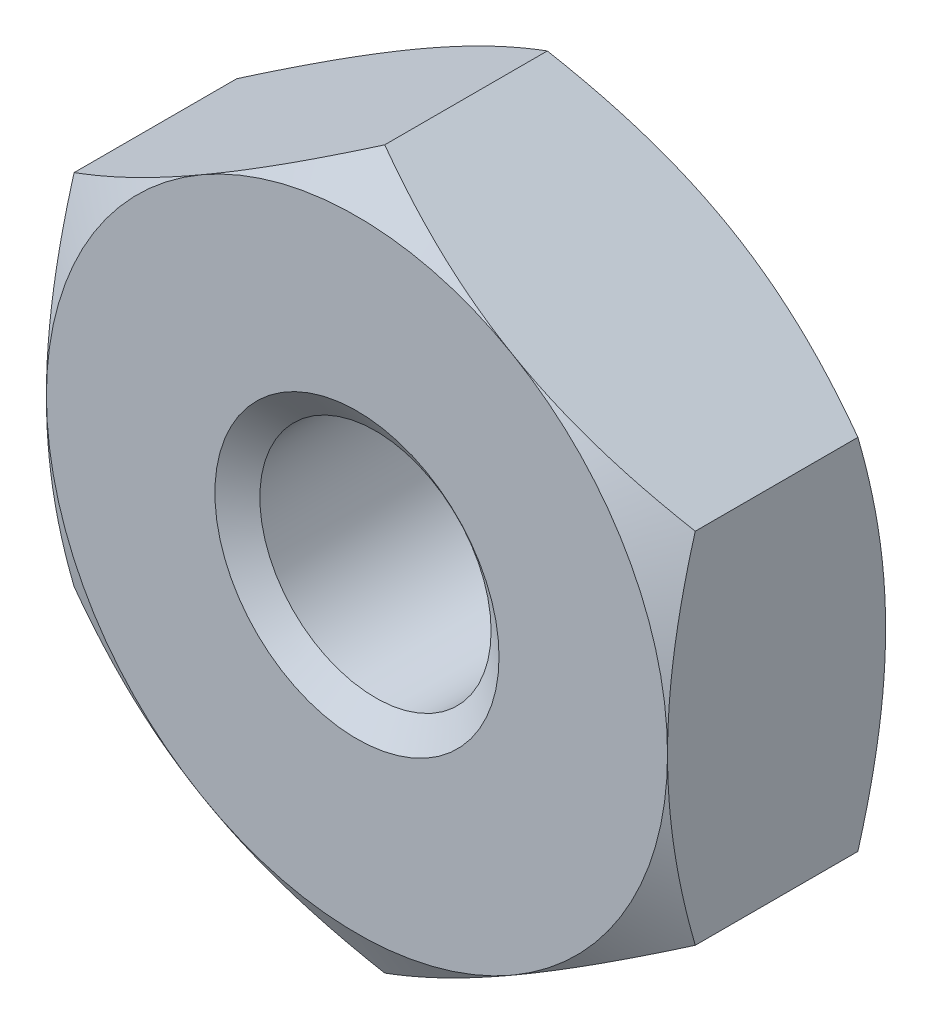
SolidWorks part; units mm, degrees
material "Alloy Steel"
ref_plane "Plane1" through (0, 0, 0) normal (0, 0, 1) x (1, 0, 0)
ref_plane "Plane2" through (0, 0, 0) normal (0, 1, 0) x (1, 0, 0)
ref_plane "Plane3" through (0, 0, 0) normal (1, 0, 0) x (0, 0, -1)
revolve "EndChamfer" cut sketch "EndChamferSketch" angle 360 about L11
sketch "EndChamferSketch" plane through (0, 0, 0) normal (1, 0, 0) x (0, 0, -1)
  line L0 (1.651, 1.0922) -> (1.4945, 0.8687)
  line L1 (1.7018, 1.0922) -> (1.651, 1.0922)
  line L2 (1.7018, 1.0922) -> (1.7018, 0.8687)
  line L3 (1.7018, 0.8687) -> (1.4945, 0.8687)
  line L6 (-0.0508, 1.0922) -> (0, 1.0922)
  line L7 (0, 1.0922) -> (0.1565, 0.8687)
  line L9 (0.1565, 0.8687) -> (-0.0508, 0.8687)
  line L10 (-0.0508, 0.8687) -> (-0.0508, 1.0922)
  line L11 (25.0375, 0) -> (38.388, 0) construction
  dimension "D1" = 35
  dimension "D2" = 0.0508
  dimension "Offset1" = 1.7018
  dimension "ThreadMajor" = 1.0922
  dimension "ChamferDepth" = 0.2235
  dimension "Offset2" = 1.7526
extrude "BaseNut" add sketch "BaseNutSke" against normal blind 1.6764
sketch "BaseNutSke" plane through (0, 0, 0) normal (0, 0, 1) x (1, 0, 0)
  line L6 (2.3876, 1.3785) -> (2.3876, -1.3785)
  line L7 (-2.3876, 1.3785) -> (-2.3876, -1.3785)
  line L8 (2.3876, 1.3785) -> (0, 2.757)
  line L9 (0, 2.757) -> (-2.3876, 1.3785)
  line L10 (-2.3876, -1.3785) -> (0, -2.757)
  line L11 (0, -2.757) -> (2.3876, -1.3785)
  circle A0 centre (0, 0) radius 0.889
  dimension "D4" = 2.3876
  dimension "Thread_min" = 1.778
  dimension "D1" = 120
  dimension "D2" = 2.3876
  dimension "D3" = 2.3876
  dimension "Width_flats" = 4.7752
cosmetic thread "ThreadCosmetic" parameters "Thread_nominal"=2.1844
sketch "Sketch3" plane through (0, 0, 0) normal (1, 0, 0) x (0, 0, -1)
  line L0 (1.6764, 2.3876) -> (1.4631, 2.757)
  line L1 (1.4631, 2.757) -> (1.4631, 15.457)
  line L2 (1.4631, 15.457) -> (14.3764, 15.457)
  line L3 (14.3764, 15.457) -> (14.3764, 2.3876)
  line L4 (14.3764, 2.3876) -> (1.6764, 2.3876)
  line L5 (1.6764, 1.3785) -> (1.6764, 2.757) construction
  line L6 (1.6764, 2.757) -> (0, 2.757) construction
  line L7 (0, 0) -> (38.6776, 0) construction
  line L8 (1.6764, 0) -> (0, 0) construction
  line L9 (0.8382, 2.757) -> (0.8382, 44.222) construction
  line L10 (0.2133, 15.457) -> (-12.7, 15.457)
  line L11 (-12.7, 15.457) -> (-12.7, 2.3876)
  line L12 (-12.7, 2.3876) -> (0, 2.3876)
  line L13 (0, 2.3876) -> (0.2133, 2.757)
  line L14 (0.2133, 2.757) -> (0.2133, 15.457)
  line L16 (1.6764, 2.757) -> (0, 2.757) construction
  dimension "D1" = 2.3876
  dimension "D2" = 30
  dimension "D3" = 12.7
  dimension "D4" = 12.7
revolve "Double-Chamfer" cut sketch "Sketch3" angle 360 about L7
equation "\"D2@BaseNutSke\" = \"Width_flats@BaseNutSke\" / 2"
equation "\"D3@BaseNutSke\" = \"Width_flats@BaseNutSke\" / 2"
equation "\"D1@Sketch3\" = \"Width_flats@BaseNutSke\" /2"
equation "\"D4@BaseNutSke\" = \"D3@BaseNutSke\""
equation "' \"Num_threads@ThdSchPat\" = \"Num_threads@ThdSchPat\" - sgn( \"Num_threads@ThdSchPat\" - 1) '---chamfered tips only---"
equation "\"ThreadMajor@EndChamferSketch\" = \"Thread_nominal@ThreadCosmetic\" * 0.5"
equation "\"ChamferDepth@EndChamferSketch\" = (\"Thread_nominal@ThreadCosmetic\" - \"Thread_min@BaseNutSke\") * 0.55"
equation "\"Offset1@EndChamferSketch\" = \"Thickness@BaseNut\" + 0.001"
equation "\"Offset2@EndChamferSketch\" = \"Offset1@EndChamferSketch\" + 0.002"
